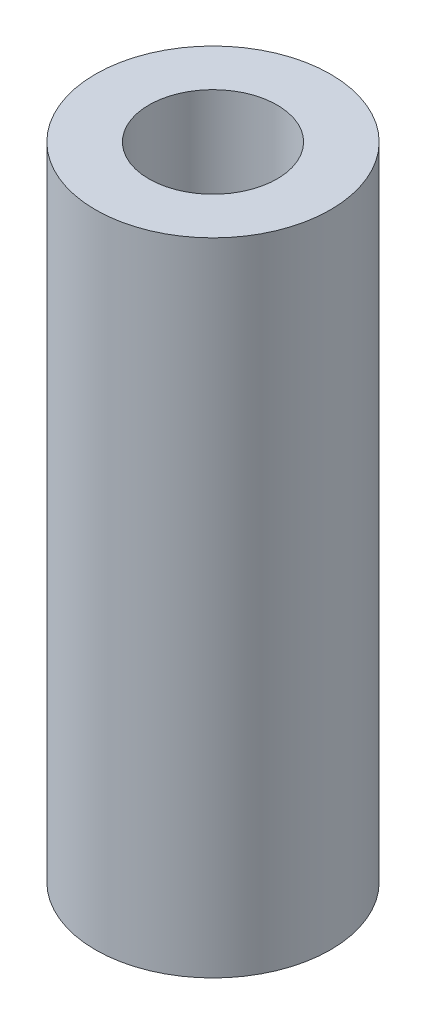
SolidWorks part; units mm, degrees
ref_plane "Front Plane" through (0, 0, 0) normal (0, 0, 1) x (1, 0, 0)
ref_plane "Top Plane" through (0, 0, 0) normal (0, 1, 0) x (1, 0, 0)
ref_plane "Right Plane" through (0, 0, 0) normal (1, 0, 0) x (0, 0, -1)
sketch "Sketch1" plane through (0, 0, 0) normal (0, 1, 0) x (1, 0, 0)
  circle A0 centre (0, 0) radius 1.8
  circle A1 centre (0, 0) radius 3.3
  dimension "D1" = 3.6
  dimension "D2" = 1.5
extrude "Boss-Extrude1" add sketch "Sketch1" along normal blind 18
